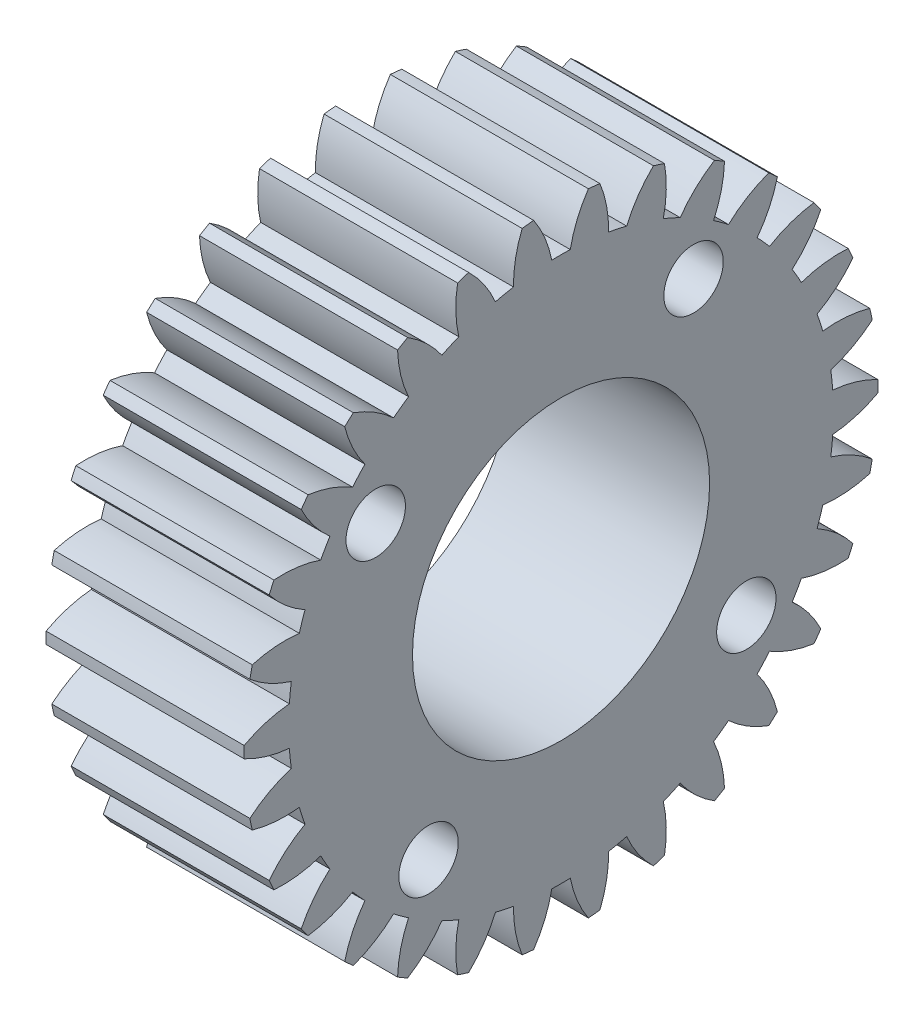
SolidWorks part; units mm, degrees
ref_plane "Plane1" through (0, 0, 0) normal (0, 0, 1) x (1, 0, 0)
ref_plane "Plane2" through (0, 0, 0) normal (0, 1, 0) x (1, 0, 0)
ref_plane "Plane3" through (0, 0, 0) normal (1, 0, 0) x (0, 0, -1)
sketch "HoldingSke" plane through (0, 0, 0) normal (0, 1, 0) x (1, 0, 0)
  line L0 (0, 0) -> (0.866, -0.5)
  line L1 (-15, 0) -> (100, 0) construction
  line L2 (0, 0) -> (-2.1039, 2.3779)
  line L3 (0, 0) -> (-11.863, 4.5341)
  line L4 (0, 0) -> (7.479, 4.318)
  line L5 (0, 0) -> (-46.8476, -17.4728)
  line L6 (0, 0) -> (-8.2896, -5.593)
  line L7 (-2.1039, 2.3779) -> (8.6586, 51.2059)
  line L8 (-76.2, 54.61) -> (-73.9, 54.61)
  line L9 (-71.009, 38.7566) -> (-53.1078, 45.2721)
  line L10 (-76.2, 71.12) -> (104.1128, 71.12)
  line L11 (0, 0) -> (-10, 0)
  line L12 (-76.2, 101.6) -> (-76.162, 101.6)
  line L13 (24.9733, 27.94) -> (52.9518, 28.4284)
  line L14 (24.9733, 27.94) -> (24.9743, 27.94)
  line L15 (24.9733, 27.94) -> (100.4006, 29.5858)
  line L16 (-63.627, -1) -> (-12.827, -1)
  circle A0 centre (0, 0) radius 7.5
  circle A1 centre (0, 0) radius 13.749
  circle A2 centre (0, 0) radius 37.5
  circle A3 centre (0, 0) radius 7.5
  dimension "MHD" = 27.498
  dimension "Hub_dia" = 75
  dimension "Bore" = 15
  dimension "MBD" = 15
  dimension "Num_teeth" = 30
  dimension "Pitch" = 1
  dimension "Overall_len" = 50
  dimension "Show_teeth" = 30
  dimension "Thickness" = 10
  dimension "OAL" = 50.0001
  dimension "T_dim" = 2.3
  dimension "Ap" = 20
  dimension "H" = 19.05
  dimension "Pitch_radius" = 180.3128
  dimension "Width" = 10
  dimension "Backlash" = 0.038
  dimension "Addendum_fac" = 1
  dimension "Dedendum_fac" = 1.25
  dimension "Clearance_fac" = 0.25
  dimension "Dedendum_add" = 0.001
  dimension "Module" = 1
sketch "BasProSke" plane through (0, 0, 0) normal (0, 1, 0) x (1, 0, 0)
  line L0 (-10, 0) -> (60, 0) construction
  line L1 (0, 0) -> (0, 16)
  line L2 (0, 0) -> (10, 0)
  line L3 (10, 0) -> (10, 16)
  line L4 (10, 16) -> (0, 16)
  dimension "Thickness" = 10
  dimension "Diameter" = 32
revolve "Base-Revolve" add sketch "BasProSke" angle 360 about L0
sketch "TooCutSke" plane through (0, 0, 0) normal (1, 0, 0) x (0, 0, -1)
  line L1 (0, 0) -> (0, 107) construction
  line L2 (0, 0) -> (-0.8515, 14.9758) construction
  line L3 (0, 0) -> (-3.1323, 29.8014) construction
  line L4 (-0.8515, 14.9758) -> (-1.5661, 14.9007) construction
  arc A0 (0.4664, 13.7411) -> (-0.4664, 13.7411) centre (0, 0) ccw
  arc A1 (1.3975, 15.9644) -> (-1.3975, 15.9644) centre (0, 0) ccw
  circle A2 centre (0, 0) radius 15 construction
  circle A3 centre (0, 0) radius 14.0954 construction
  arc A4 (-0.4664, 13.7411) -> (-1.3975, 15.9644) centre (-6.3534, 12.5823) ccw
  arc A5 (1.3975, 15.9644) -> (0.4664, 13.7411) centre (6.3534, 12.5823) ccw
  dimension "Root_dia" = 27.498
  dimension "Overcut_dia" = 32.0508
  dimension "Pitch_dia" = 30
  dimension "Base_dia" = 28.1908
  dimension "Flank_rad" = 6
  dimension "Half_ang" = 6
  dimension "Half_CT" = 0.7185
extrude "ToothCut" cut sketch "TooCutSke" along normal through all
fillet "Breaks" [suppressed] radius 0.02
fillet "RootFillets" [suppressed] radius 0.251
pattern_circular "TeethCuts" count 30 every 12 about axis through (-10, 0, 0) along (1, 0, 0) of "ToothCut", "RootFillets", "Breaks"
sketch "HubNeaOneSke" plane through (0, 0, 0) normal (-1, 0, 0) x (0, 0, 1)
  circle A0 centre (0, 0) radius 13.749
  dimension "Diameter" = 27.498
extrude "HubNearOne" [suppressed] add sketch "HubNeaOneSke" along normal blind 40.0001
sketch "HubNeaBotSke" plane through (0, 0, 0) normal (-1, 0, 0) x (0, 0, 1)
  circle A0 centre (0, 0) radius 13.749
  dimension "Diameter" = 27.498
extrude "HubNearBoth" [suppressed] add sketch "HubNeaBotSke" along normal blind 20
ref_plane "FarPln" through (10, 0, 0) normal (1, 0, 0) x (0, 0, -1)
sketch "HubFarSke" plane through (10, 0, 0) normal (1, 0, 0) x (0, 0, -1)
  circle A0 centre (0, 0) radius 13.749
  dimension "Diameter" = 27.498
extrude "HubFar" [suppressed] add sketch "HubFarSke" along normal blind 20
sketch "BorSke" plane through (0, 0, 0) normal (1, 0, 0) x (0, 0, -1)
  circle A0 centre (0, 0) radius 7.5
  dimension "Diameter" = 15
extrude "Bore" cut sketch "BorSke" along normal mid plane 100.0001
sketch "KeySke" plane through (0, 0, 0) normal (1, 0, 0) x (0, 0, -1)
  line L0 (-2.5, 0) -> (-2.5, 9.8)
  line L1 (-2.5, 9.8) -> (2.5, 9.8)
  line L2 (2.5, 9.8) -> (2.5, 0)
  line L3 (0, 0) -> (0, 34) construction
  line L4 (-2.5, 0) -> (2.5, 0)
  dimension "Offset" = 9.8
  dimension "Width" = 5
extrude "Keyway" [suppressed] cut sketch "KeySke" along normal mid plane 100.0001
pattern_circular "Keyway2" [suppressed] count 2 every 90 about axis through (-10, 0, 0) along (1, 0, 0)
sketch "Sketch1" plane through (0, 0, 0) normal (-1, 0, 0) x (0, 0, 1)
  circle A1 centre (6.6893, -9.3543) radius 1.5
  circle A2 centre (6.6893, -9.3543) radius 1.5
  circle A3 centre (9.3543, 6.6893) radius 1.5
  circle A4 centre (9.3543, 6.6893) radius 1.5
  circle A9 centre (-6.6893, 9.3543) radius 1.5
  circle A10 centre (-6.6893, 9.3543) radius 1.5
  circle A11 centre (-9.3543, -6.6893) radius 1.5
  circle A12 centre (-9.3543, -6.6893) radius 1.5
  dimension "D1" = 0
  dimension "D2" = 0
  dimension "D5" = 0
  dimension "D6" = 0
extrude "Cut-Extrude1" cut sketch "Sketch1" against normal through all
equation "' \"Module@HoldingSke\" = 6.35"
equation "' \"Num_teeth@HoldingSke\" = 12"
equation "' \"Ap@HoldingSke\" =  20"
equation "' \"Ap@HoldingSke\" = 20"
equation "' \"Width@HoldingSke\" = 0.5 * 25.4"
equation "' \"Hub_dia@HoldingSke\"= 1 * 25.4"
equation "' \"Hub_dia@HoldingSke\" = 1 * 25.4"
equation "' \"Overall_len@HoldingSke\" = 1.0 * 25.4"
equation "' \"Bore@HoldingSke\" = 0.75 * 25.4"
equation "' \"T_dim@HoldingSke\" = 0.1 * 25.4"
equation "' \"Width@KeySke\" = 0.25 * 25.4"
equation "' \"Show_teeth@HoldingSke\" = 13"
equation "' \"Backlash@HoldingSke\" = 0.009 * 25.4"
equation "' \"Addendum_fac@HoldingSke\" = 1.0"
equation "' \"Dedendum_fac@HoldingSke\" = 1.25"
equation "' \"Dedendum_add@HoldingSke\" = 0.00005 * 25.4"
equation "' \"Clearance_fac@HoldingSke\" = 0.25"
equation "\"Pitch@HoldingSke\" = 1 / \"Module@HoldingSke\""
equation "\"Overcut_dia@TooCutSke\" = (\"Num_teeth@HoldingSke\" + 2 * \"Addendum_fac@HoldingSke\") / \"Pitch@HoldingSke\" + 0.002 * 25.4"
equation "\"Pitch_dia@TooCutSke\" = \"Num_teeth@HoldingSke\" / \"Pitch@HoldingSke\""
equation "\"Base_dia@TooCutSke\" = \"Num_teeth@HoldingSke\" / \"Pitch@HoldingSke\" * cos((\"Ap@HoldingSke\"  * 3.14159265 / 180))"
equation "\"Root_dia@TooCutSke\" = (\"Num_teeth@HoldingSke\" + 2) / \"Pitch@HoldingSke\" - 2 * (\"Addendum_fac@HoldingSke\" + \"Dedendum_fac@HoldingSke\") / \"Pitch@HoldingSke\" - \"Dedendum_add@HoldingSke\" * 2"
equation "\"Half_ang@TooCutSke\" = 180 / \"Num_teeth@HoldingSke\""
equation "\"Half_CT@TooCutSke\" = \"Num_teeth@HoldingSke\" / \"Pitch@HoldingSke\" * sin((3.14159265 / 2 / \"Num_teeth@HoldingSke\")) / 2 - 7 * \"Backlash@HoldingSke\" / 4"
equation "\"Flank_rad@TooCutSke\" = \"Num_teeth@HoldingSke\" / \"Pitch@HoldingSke\" / 5"
equation "\"Radius@RootFillets\" = \"Clearance_fac@HoldingSke\" / \"Pitch@HoldingSke\" + \"Dedendum_add@HoldingSke\""
equation "\"Break_rad@Breaks\" = 0.02 / \"Pitch@HoldingSke\""
equation "\"Thickness@HoldingSke\" = \"Width@HoldingSke\""
equation "\"OAL@HoldingSke\" = \"Thickness@HoldingSke\""
equation "\"MHD@HoldingSke\" = (\"Num_teeth@HoldingSke\" + 2) / \"Pitch@HoldingSke\" - 2 * (\"Addendum_fac@HoldingSke\" + \"Dedendum_fac@HoldingSke\")  / \"Pitch@HoldingSke\" - \"Dedendum_add@HoldingSke\" * 2"
equation "\"MBD@HoldingSke\" = (\"Num_teeth@HoldingSke\" + 2) / \"Pitch@HoldingSke\" - 2 * (\"Addendum_fac@HoldingSke\" + \"Dedendum_fac@HoldingSke\")  / \"Pitch@HoldingSke\" - \"Dedendum_add@HoldingSke\" * 2 - 0.002 * 25.4"
equation "\"MHD@HoldingSke\" = ((sgn( \"MHD@HoldingSke\" - \"Hub_dia@HoldingSke\" )-1)*( \"MHD@HoldingSke\" - \"Hub_dia@HoldingSke\" ))/-2+ \"Hub_dia@HoldingSke\""
equation "\"MBD@HoldingSke\" = ((sgn( \"MBD@HoldingSke\" - \"Bore@HoldingSke\" )-1)*( \"MBD@HoldingSke\" - \"Bore@HoldingSke\" ))/-2+ \"Bore@HoldingSke\""
equation "\"OAL@HoldingSke\" = ((sgn( \"OAL@HoldingSke\" - \"Overall_len@HoldingSke\" )+1)*( \"OAL@HoldingSke\" - \"Overall_len@HoldingSke\" ))/2 + \"Overall_len@HoldingSke\" + 0.000002 * 25.4"
equation "\"Num_teeth@TeethCuts\" = int( \"Show_teeth@HoldingSke\" ) + 1"
equation "\"Num_teeth@TeethCuts\" = ((sgn( \"Num_teeth@TeethCuts\" - \"Num_teeth@HoldingSke\" )-1)*( \"Num_teeth@TeethCuts\" - \"Num_teeth@HoldingSke\" ))/-2+ \"Num_teeth@HoldingSke\""
equation "\"Num_teeth@TeethCuts\" = ((sgn( \"Num_teeth@TeethCuts\" - 2.0)+1)*( \"Num_teeth@TeethCuts\" - 2.0))/2 +2.0"
equation "\"Angle@TeethCuts\" = 360.0 / \"Num_teeth@HoldingSke\""
equation "\"Diameter@BasProSke\" = (\"Num_teeth@HoldingSke\" + 2 * \"Addendum_fac@HoldingSke\") / \"Pitch@HoldingSke\""
equation "\"Thickness@BasProSke\"  = \"Thickness@HoldingSke\""
equation "' \"Fillet_rad@BasProSke\" =  \"Thickness@HoldingSke\" * 0.05"
equation "' \"Fillet_rad@BasProSke\" = \"Thickness@HoldingSke\" * 0.05"
equation "\"MHD@HoldingSke\" = ((sgn( \"MHD@HoldingSke\" - \"Root_dia@TooCutSke\" )-1)*( \"MHD@HoldingSke\" - \"Root_dia@TooCutSke\" ))/-2+ \"Root_dia@TooCutSke\""
equation "\"Diameter@HubNeaOneSke\" = \"MHD@HoldingSke\""
equation "\"Length@HubNearOne\" = \"OAL@HoldingSke\" - \"Thickness@BasProSke\""
equation "\"Diameter@HubNeaBotSke\" = \"MHD@HoldingSke\""
equation "\"Length@HubNearBoth\" = ( \"OAL@HoldingSke\" - \"Thickness@BasProSke\" ) / 2.0"
equation "\"Thickness@FarPln\" = \"Thickness@BasProSke\""
equation "\"Diameter@HubFarSke\" = \"MHD@HoldingSke\""
equation "\"Length@HubFar\" = ( \"OAL@HoldingSke\" - \"Thickness@BasProSke\" ) / 2.0"
equation "\"Diameter@BorSke\" = \"MBD@HoldingSke\""
equation "\"D1@Bore\" = \"OAL@HoldingSke\" * 2.0"
equation "\"D1@Keyway\" = \"OAL@HoldingSke\" * 2.0"
equation "\"Offset@KeySke\" = \"T_dim@HoldingSke\" + \"MBD@HoldingSke\" / 2.0"
